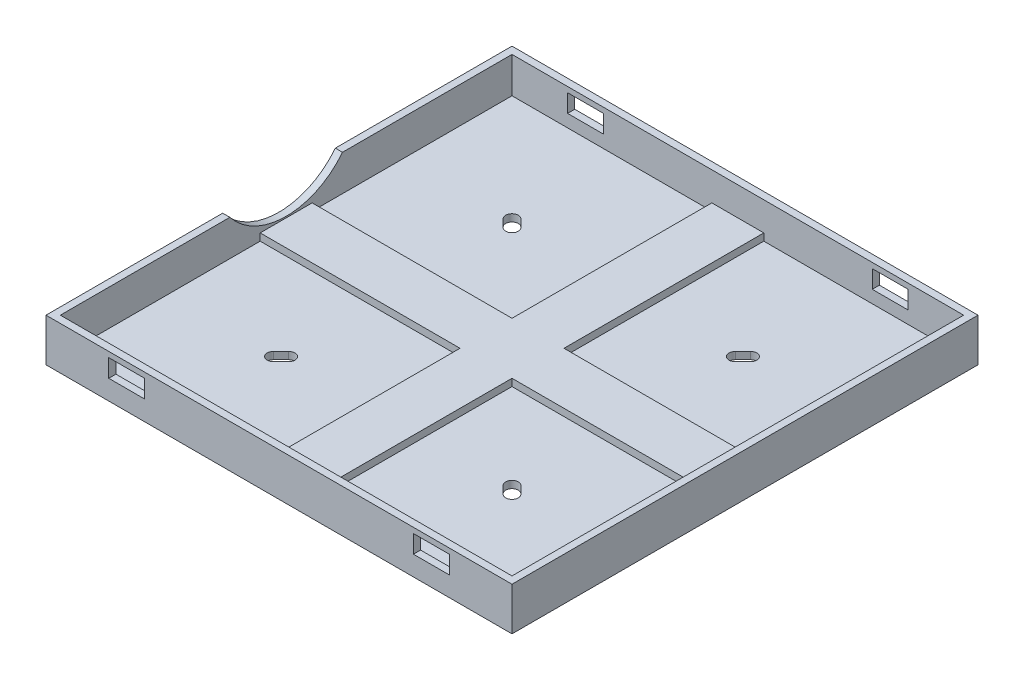
SolidWorks part; units mm, degrees
material "PLA+"
ref_plane "Front Plane" through (0, 0, 0) normal (0, 0, 1) x (1, 0, 0)
ref_plane "Top Plane" through (0, 0, 0) normal (0, 1, 0) x (1, 0, 0)
ref_plane "Right Plane" through (0, 0, 0) normal (1, 0, 0) x (0, 0, -1)
ref_plane "Plane1" through (0, 15.8239, 0) normal (0, 1, 0) x (1, 0, 0)
sketch "Sketch1" plane through (0, 15.8239, 0) normal (0, 1, 0) x (1, 0, 0)
  line L0 (46.104, 114.4443) -> (-213.896, 114.4443)
  line L1 (-213.896, 114.4443) -> (-213.896, -145.5557)
  line L2 (-213.896, -145.5557) -> (46.104, -145.5557)
  line L3 (46.104, -145.5557) -> (46.104, 114.4443)
extrude "Boss-Extrude1" add sketch "Sketch1" against normal blind 24
sketch "Sketch2" plane through (0, 15.8239, 0) normal (0, 1, 0) x (-1, 0, 0)
  line L0 (-42.104, -110.4443) -> (209.896, -110.4443)
  line L1 (209.896, -110.4443) -> (209.896, 141.5557)
  line L2 (209.896, 141.5557) -> (-42.104, 141.5557)
  line L3 (-42.104, 141.5557) -> (-42.104, -110.4443)
extrude "Cut-Extrude1" cut sketch "Sketch2" against normal blind 16
sketch "Sketch3" plane through (0, -0.1761, 0) normal (0, 1, 0) x (-1, 0, 0)
  line L0 (-42.104, 141.5557) -> (-42.104, 30.0557)
  line L1 (-42.104, 30.0557) -> (69.396, 30.0557)
  line L2 (69.396, 30.0557) -> (69.396, 141.5557)
  line L3 (69.396, 141.5557) -> (-42.104, 141.5557)
extrude "Cut-Extrude2" cut sketch "Sketch3" against normal blind 4
sketch "Sketch4" plane through (0, -0.1761, 0) normal (0, 1, 0) x (-1, 0, 0)
  line L0 (98.396, 141.5557) -> (98.396, 30.0557)
  line L1 (98.396, 30.0557) -> (209.896, 30.0557)
  line L2 (209.896, 30.0557) -> (209.896, 141.5557)
  line L3 (209.896, 141.5557) -> (98.396, 141.5557)
extrude "Cut-Extrude3" cut sketch "Sketch4" against normal blind 4
sketch "Sketch5" plane through (0, -0.1761, 0) normal (0, 1, 0) x (-1, 0, 0)
  line L0 (209.896, 1.0557) -> (98.396, 1.0557)
  line L1 (98.396, 1.0557) -> (98.396, -110.4443)
  line L2 (98.396, -110.4443) -> (209.896, -110.4443)
  line L3 (209.896, -110.4443) -> (209.896, 1.0557)
extrude "Cut-Extrude4" cut sketch "Sketch5" against normal blind 4
sketch "Sketch6" plane through (0, -0.1761, 0) normal (0, 1, 0) x (-1, 0, 0)
  line L0 (69.396, 1.0557) -> (-42.104, 1.0557)
  line L1 (-42.104, 1.0557) -> (-42.104, -110.4443)
  line L2 (-42.104, -110.4443) -> (69.396, -110.4443)
  line L3 (69.396, -110.4443) -> (69.396, 1.0557)
extrude "Cut-Extrude5" cut sketch "Sketch6" against normal blind 4
sketch "Sketch7" plane through (-209.896, 0, 0) normal (1, 0, 0) x (0, 0, -1)
  line L0 (15.8679, 15.8239) -> (-46.9792, 15.8239)
  arc A0 (-46.9792, 15.8239) -> (15.8679, 15.8239) centre (-15.5557, 40.5739) ccw
extrude "Cut-Extrude6" cut sketch "Sketch7" against normal through all
sketch "Sketch8" plane through (0, 0, 141.5557) normal (0, 0, -1) x (-1, 0, 0)
  line L0 (178.896, 2.8239) -> (178.896, 12.8239)
  line L1 (178.896, 12.8239) -> (158.896, 12.8239)
  line L2 (158.896, 12.8239) -> (158.896, 2.8239)
  line L3 (158.896, 2.8239) -> (178.896, 2.8239)
extrude "Cut-Extrude7" cut sketch "Sketch8" against normal through all
sketch "Sketch9" plane through (0, -4.1761, 0) normal (0, 1, 0) x (-1, 0, 0)
  line L0 (24.0719, 80.3295) -> (19.8292, 84.5722)
  line L1 (14.8795, 79.6224) -> (19.1221, 75.3798)
  arc A0 (19.8292, 84.5722) -> (14.8795, 79.6224) centre (17.3544, 82.0973) ccw
  arc A1 (19.1221, 75.3798) -> (24.0719, 80.3295) centre (21.597, 77.8546) ccw
extrude "Cut-Extrude8" cut sketch "Sketch9" against normal through all
sketch "Sketch10" plane through (0, -4.1761, 0) normal (0, 1, 0) x (-1, 0, 0)
  line L0 (147.9628, 84.5722) -> (143.7201, 80.3295)
  line L1 (148.6699, 75.3798) -> (152.9125, 79.6224)
  arc A0 (143.7201, 80.3295) -> (148.6699, 75.3798) centre (146.195, 77.8546) ccw
  arc A1 (152.9125, 79.6224) -> (147.9628, 84.5722) centre (150.4376, 82.0973) ccw
extrude "Cut-Extrude9" cut sketch "Sketch10" against normal through all
sketch "Sketch11" plane through (0, 0, 145.5557) normal (0, 0, 1) x (1, 0, 0)
  line L0 (-8.896, 2.8239) -> (11.104, 2.8239)
  line L1 (11.104, 2.8239) -> (11.104, 12.8239)
  line L2 (11.104, 12.8239) -> (-8.896, 12.8239)
  line L3 (-8.896, 12.8239) -> (-8.896, 2.8239)
extrude "Cut-Extrude10" cut sketch "Sketch11" against normal up to next
sketch "Sketch12" plane through (0, 0, -110.4443) normal (0, 0, 1) x (1, 0, 0)
  line L0 (-178.896, 12.8239) -> (-178.896, 2.8239)
  line L1 (-178.896, 2.8239) -> (-158.896, 2.8239)
  line L2 (-158.896, 2.8239) -> (-158.896, 12.8239)
  line L3 (-158.896, 12.8239) -> (-178.896, 12.8239)
extrude "Cut-Extrude11" cut sketch "Sketch12" against normal through all
sketch "Sketch13" plane through (0, -4.1761, 0) normal (0, 1, 0) x (-1, 0, 0)
  line L0 (19.8292, -53.4609) -> (24.0719, -49.2182)
  line L1 (19.1221, -44.2685) -> (14.8795, -48.5111)
  arc A0 (24.0719, -49.2182) -> (19.1221, -44.2685) centre (21.597, -46.7433) ccw
  arc A1 (14.8795, -48.5111) -> (19.8292, -53.4609) centre (17.3544, -50.986) ccw
extrude "Cut-Extrude12" cut sketch "Sketch13" against normal through all
sketch "Sketch14" plane through (0, 0, -110.4443) normal (0, 0, 1) x (1, 0, 0)
  line L0 (11.104, 2.8239) -> (11.104, 12.8239)
  line L1 (11.104, 12.8239) -> (-8.896, 12.8239)
  line L2 (-8.896, 12.8239) -> (-8.896, 2.8239)
  line L3 (-8.896, 2.8239) -> (11.104, 2.8239)
extrude "Cut-Extrude13" cut sketch "Sketch14" against normal through all
sketch "Sketch15" plane through (0, -8.1761, 0) normal (0, -1, 0) x (1, 0, 0)
  line L0 (-148.6699, -44.2685) -> (-152.9125, -48.5111)
  line L1 (-147.9628, -53.4609) -> (-143.7201, -49.2182)
  arc A0 (-143.7201, -49.2182) -> (-148.6699, -44.2685) centre (-146.195, -46.7433) ccw
  arc A1 (-152.9125, -48.5111) -> (-147.9628, -53.4609) centre (-150.4376, -50.986) ccw
extrude "Cut-Extrude14" cut sketch "Sketch15" against normal through all
